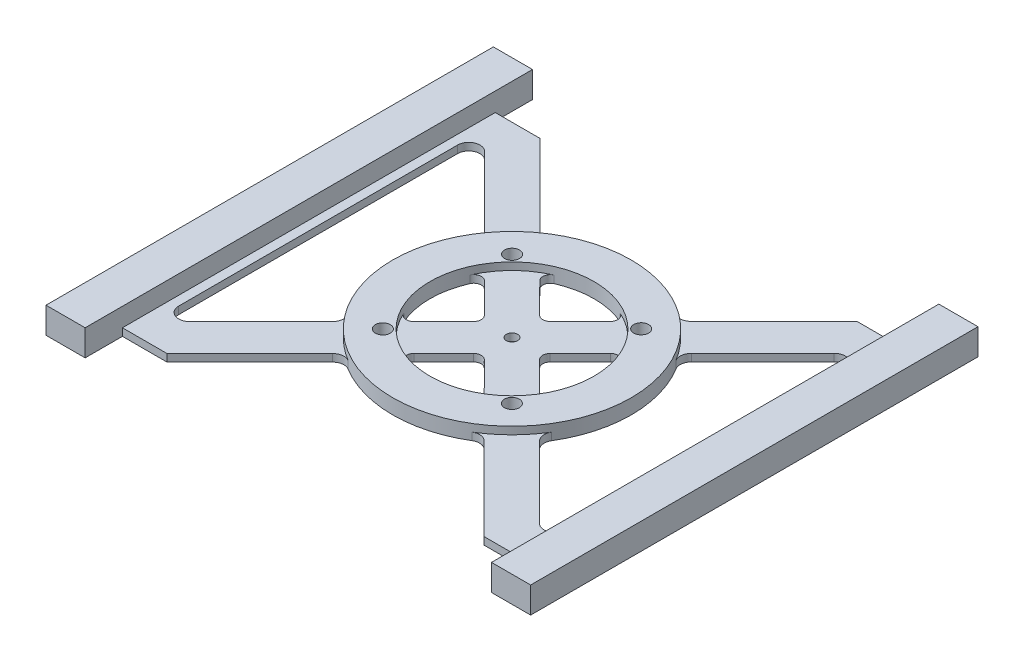
SolidWorks part; units mm, degrees
ref_plane "Front Plane" through (0, 0, 0) normal (0, 0, 1) x (1, 0, 0)
ref_plane "Top Plane" through (0, 0, 0) normal (0, 1, 0) x (1, 0, 0)
ref_plane "Right Plane" through (0, 0, 0) normal (1, 0, 0) x (0, 0, -1)
sketch "Sketch1" plane through (0, 0, 0) normal (0, 1, 0) x (1, 0, 0)
  circle A0 centre (0, 0) radius 22
  circle A1 centre (0, 0) radius 22
  circle A2 centre (0, 0) radius 32
  dimension "D1" = 44
  dimension "D2" = 44
  dimension "D3" = 64
extrude "Boss-Extrude2" add sketch "Sketch1" along normal blind 4 contours A2 A0
sketch "Sketch3" plane through (0, 0, 0) normal (0, 1, 0) x (1, 0, 0)
  line L1 (-65, -60) -> (-54.5, -60)
  line L2 (-65, -60) -> (-65, 60)
  line L3 (-65, 60) -> (-54.5, 60)
  line L4 (-54.5, -60) -> (-54.5, 60)
  line L5 (54.5, -60) -> (65, -60)
  line L6 (54.5, -60) -> (54.5, 60)
  line L7 (54.5, 60) -> (65, 60)
  line L8 (65, -60) -> (65, 60)
  point P8 (54.5, 0)
  point P10 (-54.5, 0)
  dimension "D1" = 120
  dimension "D2" = 10.5
  dimension "D3" = 130
  dimension "D4" = 10.5
  dimension "D5" = 54.5
  dimension "D6" = 120
extrude "Boss-Extrude4" add sketch "Sketch3" along normal blind 7 separate body
sketch "Sketch4" plane through (0, 0, 0) normal (0, 1, 0) x (1, 0, 0)
  line L0 (-54.5, 50) -> (-42.5, 50)
  line L1 (-54.5, -60) -> (-54.5, 60) construction
  line L2 (-42.5, 50) -> (-20.3164, 27.7803)
  line L3 (54.5, -50) -> (42.5, -50)
  line L4 (54.5, 60) -> (54.5, -60) construction
  line L5 (42.5, -50) -> (20.3164, -27.7803)
  line L6 (-54.5, 60) -> (-65, 60) construction
  line L7 (54.5, -60) -> (65, -60) construction
  line L8 (-52, -37.4031) -> (-52, 37.4031)
  line L9 (52, -37.4031) -> (52, 37.4031)
  line L10 (-54.5, -50) -> (-42.5, -50)
  line L11 (-54.5, -60) -> (-54.5, 60) construction
  line L12 (54.5, 50) -> (42.5, 50)
  line L13 (42.5, 50) -> (20.3164, 27.7803)
  line L14 (-42.5, -50) -> (-20.3164, -27.7803)
  line L15 (-8.8293, -1.4131) -> (-16.8848, -9.4817)
  line L16 (8.8293, -1.4131) -> (16.8848, -9.4817)
  line L17 (8.8293, 1.4131) -> (16.8848, 9.4817)
  line L18 (-8.8293, 1.4131) -> (-16.8848, 9.4817)
  line L19 (-27.7471, 20.3617) -> (-46.877, 39.5227)
  line L20 (-9.4542, 16.9003) -> (-1.4154, 8.8484)
  line L21 (9.4542, 16.9003) -> (1.4154, 8.8484)
  line L22 (27.7471, 20.3617) -> (46.877, 39.5227)
  line L23 (27.7471, -20.3617) -> (46.877, -39.5227)
  line L24 (9.4542, -16.9003) -> (1.4154, -8.8484)
  line L25 (-9.4542, -16.9003) -> (-1.4154, -8.8484)
  line L26 (-27.7471, -20.3617) -> (-46.877, -39.5227)
  line L27 (-54.5, -50) -> (-54.5, 50)
  line L28 (54.5, -50) -> (54.5, 50)
  arc A0 (46.877, -39.5227) -> (52, -37.4031) centre (49, -37.4031) ccw
  arc A1 (46.877, 39.5227) -> (52, 37.4031) centre (49, 37.4031) cw
  arc A2 (-52, 37.4031) -> (-46.877, 39.5227) centre (-49, 37.4031) cw
  arc A3 (-46.877, -39.5227) -> (-52, -37.4031) centre (-49, -37.4031) cw
  arc A4 (-16.634, -27.337) -> (16.634, -27.337) centre (0, 0) ccw
  arc A5 (-8.8427, -20.1447) -> (8.8427, -20.1447) centre (0, 0) ccw
  arc A6 (20.1302, -8.8755) -> (20.1302, 8.8755) centre (0, 0) ccw
  arc A7 (27.3099, -16.6785) -> (27.3099, 16.6785) centre (0, 0) ccw
  arc A8 (8.8427, 20.1447) -> (-8.8427, 20.1447) centre (0, 0) ccw
  arc A9 (16.634, 27.337) -> (-16.634, 27.337) centre (0, 0) ccw
  arc A10 (-20.1302, 8.8755) -> (-20.1302, -8.8755) centre (0, 0) ccw
  arc A11 (-27.3099, 16.6785) -> (-27.3099, -16.6785) centre (0, 0) ccw
  arc A12 (-16.634, -27.337) -> (-20.3164, -27.7803) centre (-18.1934, -29.8998) ccw
  arc A13 (16.634, -27.337) -> (20.3164, -27.7803) centre (18.1934, -29.8998) cw
  arc A14 (27.3099, -16.6785) -> (27.7471, -20.3617) centre (29.8702, -18.2421) ccw
  arc A15 (27.3099, 16.6785) -> (27.7471, 20.3617) centre (29.8702, 18.2421) cw
  arc A16 (16.634, 27.337) -> (20.3164, 27.7803) centre (18.1934, 29.8998) ccw
  arc A17 (-16.634, 27.337) -> (-20.3164, 27.7803) centre (-18.1934, 29.8998) cw
  arc A18 (-27.3099, 16.6785) -> (-27.7471, 20.3617) centre (-29.8702, 18.2421) ccw
  arc A19 (-27.7471, -20.3617) -> (-27.3099, -16.6785) centre (-29.8702, -18.2421) ccw
  arc A20 (8.8427, 20.1447) -> (9.4542, 16.9003) centre (8.0388, 18.3133) cw
  arc A21 (20.1302, 8.8755) -> (16.8848, 9.4817) centre (18.3002, 8.0686) ccw
  arc A22 (20.1302, -8.8755) -> (16.8848, -9.4817) centre (18.3002, -8.0686) cw
  arc A23 (8.8427, -20.1447) -> (9.4542, -16.9003) centre (8.0388, -18.3133) ccw
  arc A24 (-8.8427, -20.1447) -> (-9.4542, -16.9003) centre (-8.0388, -18.3133) cw
  arc A25 (-16.8848, -9.4817) -> (-20.1302, -8.8755) centre (-18.3002, -8.0686) cw
  arc A26 (-20.1302, 8.8755) -> (-16.8848, 9.4817) centre (-18.3002, 8.0686) cw
  arc A27 (-8.8427, 20.1447) -> (-9.4542, 16.9003) centre (-8.0388, 18.3133) ccw
  arc A28 (-1.4154, -8.8484) -> (1.4154, -8.8484) centre (0, -10.2614) cw
  arc A29 (8.8293, -1.4131) -> (8.8293, 1.4131) centre (10.2447, 0) cw
  arc A30 (1.4154, 8.8484) -> (-1.4154, 8.8484) centre (0, 10.2614) cw
  arc A31 (-8.8293, -1.4131) -> (-8.8293, 1.4131) centre (-10.2447, 0) ccw
  point P52 (-94.3848, 26.0483)
  point P59 (26.018, -18.6297)
  point P62 (26.018, 18.6297)
  point P69 (-26.018, 18.6297)
  point P72 (-26.018, -18.6297)
  point P75 (11.3793, 18.8285)
  point P82 (11.3793, -18.8285)
  point P85 (-11.3793, -18.8285)
  point P92 (-11.3793, 18.8285)
  point P97 (7.4186, 0)
  point P102 (-7.4186, 0)
  dimension "D9" = 3
  dimension "D10" = 44
  dimension "D11" = 64
  dimension "D12" = 3
  dimension "D13" = 2
  dimension "D1" = 10.5
  dimension "D2" = 10
  dimension "D3" = 10
  dimension "D4" = 2.5
  dimension "D5" = 2.5
  dimension "D6" = 12
  dimension "D7" = 12
  dimension "D8" = 10.5
extrude "Boss-Extrude5" add sketch "Sketch4" along normal blind 2 contours L28 L12 L13 A16 A9 A17 L2 L0 L27 L10 L14 A12 A4 A13 L5 L3 | A3 L8 A2 L19 A18 A11 A19 L26 | A0 L9 A1 L22 A15 A7 A14 L23 | L17 A21 A6 A22 L16 A29 | A31 L18 A26 A10 A25 L15 | A30 L21 A20 A8 A27 L20 | L24 A28 L25 A24 A5 A23
sketch "Sketch5" plane through (0, 2, 0) normal (0, 1, 0) x (1, 0, 0)
  circle A0 centre (0, 0) radius 1.5
  dimension "D1" = 3
extrude "Cut-Extrude1" cut sketch "Sketch5" against normal blind 4
sketch "Sketch6" plane through (0, 0, 0) normal (0, -1, 0) x (1, 0, 0)
  line L1 (-27.7471, 20.3617) -> (-46.877, 39.5227) construction
  line L2 (42.5, 50) -> (20.3164, 27.7803) construction
  line L3 (27.7471, -20.3617) -> (46.877, -39.5227) construction
  circle A0 centre (-17.31, -17.3382) radius 2
  circle A1 centre (17.31, -17.3382) radius 2
  circle A2 centre (17.31, 17.3382) radius 2
  circle A3 centre (-17.31, 17.3382) radius 2
  circle A5 centre (0, 0) radius 1.5 construction
  point P16 (0, 0)
  point P17 (0, 0)
  point P18 (0, 0)
  point P19 (0, 0)
  dimension "D5" = 4
  dimension "D6" = 4
  dimension "D7" = 4
  dimension "D8" = 4
  dimension "D1" = 24.5
  dimension "D2" = 5.25
  dimension "D3" = 5.25
  dimension "D4" = 5.25
extrude "Cut-Extrude2" cut sketch "Sketch6" against normal blind 4
